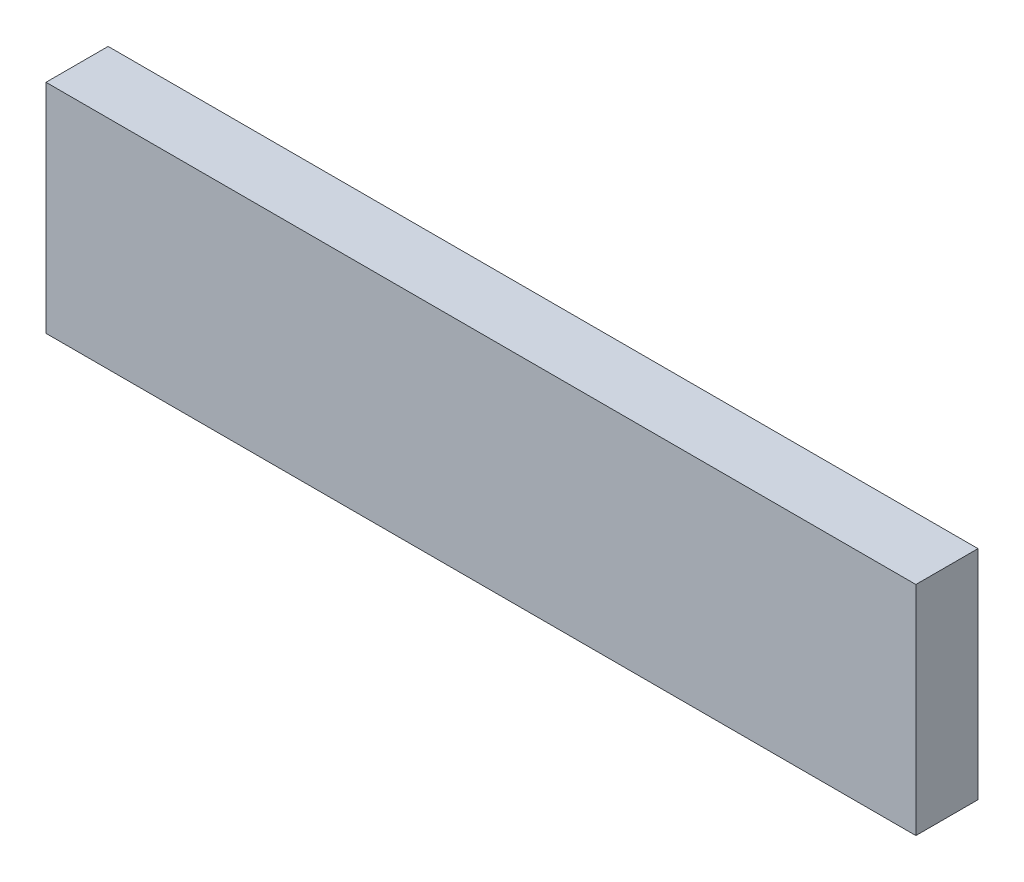
SolidWorks part; units mm, degrees
ref_plane "前视基准面" through (0, 0, 0) normal (0, 0, 1) x (1, 0, 0)
ref_plane "上视基准面" through (0, 0, 0) normal (0, 1, 0) x (1, 0, 0)
ref_plane "右视基准面" through (0, 0, 0) normal (1, 0, 0) x (0, 0, -1)
other "Configuration Table"
sketch "草图1" plane through (0, 0, 0) normal (0, 0, 1) x (1, 0, 0)
  line L1 (-140, -35) -> (140, -35)
  line L2 (-140, -35) -> (-140, 35)
  line L3 (-140, 35) -> (140, 35)
  line L4 (140, -35) -> (140, 35)
  line L5 (-140, -35) -> (140, 35) construction
  line L6 (-140, 35) -> (140, -35) construction
  point P0 (0, 0)
extrude "凸台-拉伸1" add sketch "草图1" along normal blind 20
